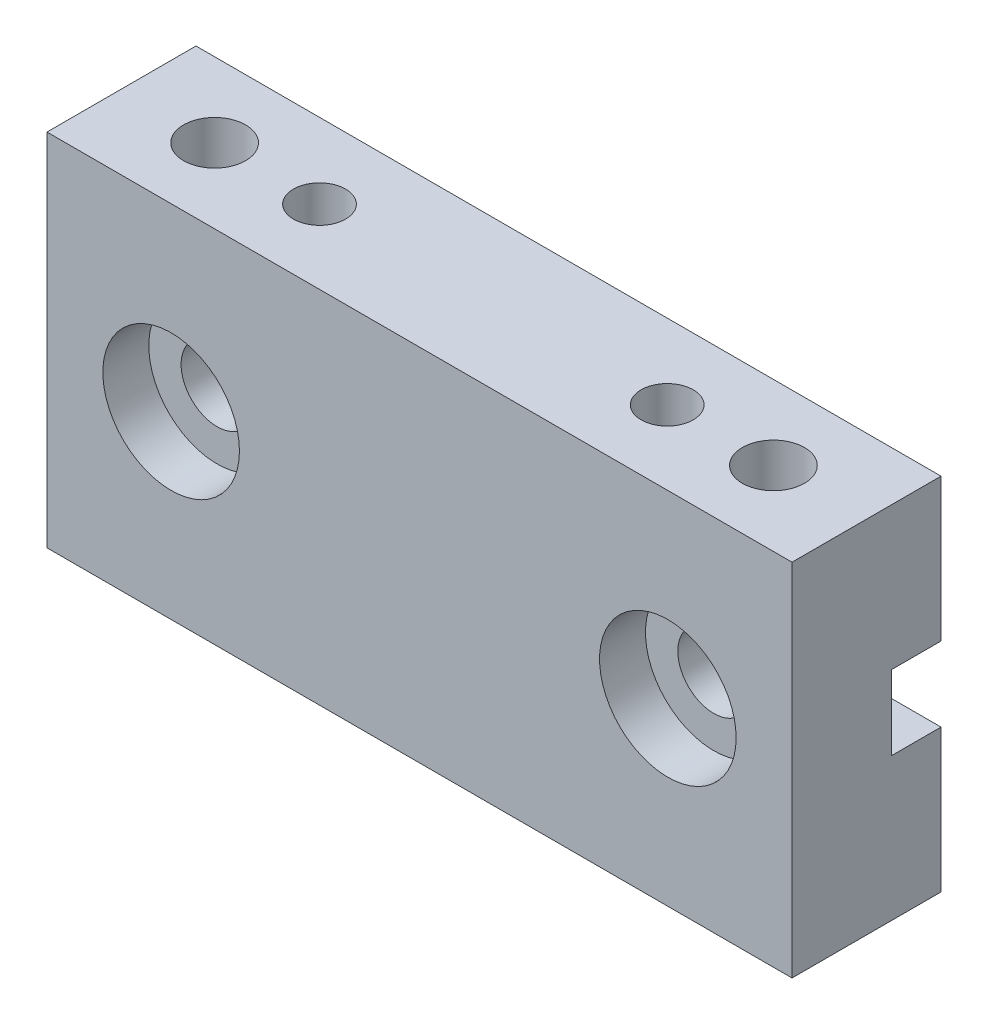
SolidWorks part; units mm, degrees
ref_plane "Front Plane" through (0, 0, 0) normal (0, 0, 1) x (1, 0, 0)
ref_plane "Top Plane" through (0, 0, 0) normal (0, 1, 0) x (1, 0, 0)
ref_plane "Right Plane" through (0, 0, 0) normal (1, 0, 0) x (0, 0, -1)
sketch "Sketch1" plane through (0, 0, 0) normal (0, 1, 0) x (1, 0, 0)
  line L1 (0, 0) -> (60, 0)
  line L2 (0, 0) -> (0, 12)
  line L3 (0, 12) -> (60, 12)
  line L4 (60, 0) -> (60, 12)
  dimension "D1" = 12
  dimension "D2" = 60
extrude "Boss-Extrude1" add sketch "Sketch1" along normal blind 11.5 contours L2 L3 L4 L1
sketch "Sketch4" plane through (0, 0, 0) normal (0, 1, 0) x (1, 0, 0)
  line L0 (60, 0) -> (60, 12) construction
  line L1 (0, 0) -> (60, 0)
  line L2 (0, 0) -> (0, 8)
  line L3 (0, 8) -> (60, 8)
  line L4 (60, 0) -> (60, 8)
  dimension "D1" = 8
extrude "Boss-Extrude2" add sketch "Sketch4" along normal blind 17.5 contours L3 L4 L1 L2
sketch "Sketch9" plane through (0, 0, 0) normal (1, 0, 0) x (0, 0, -1)
  line L1 (0, 17.5) -> (12, 17.5)
  line L2 (0, 17.5) -> (0, 29)
  line L3 (0, 29) -> (12, 29)
  line L4 (12, 17.5) -> (12, 29)
  dimension "D1" = 11.5
  dimension "D2" = 12
extrude "Boss-Extrude3" add sketch "Sketch9" along normal blind 60
sketch "Sketch10" plane through (0, 0, 0) normal (0, 0, 1) x (1, 0, 0)
  line L0 (60, 14.5) -> (0, 14.5) construction
  line L1 (60, 17.5) -> (60, 11.5) construction
  line L2 (0, 17.5) -> (0, 11.5) construction
  line L3 (50, 18.9581) -> (50, 10.0419) construction
  line L4 (10, 18.9581) -> (10, 10.0419) construction
  point P10 (-12.0778, 24.6861)
  point P11 (10, 14.5)
  point P12 (50, 14.5)
  dimension "D1" = 10
  dimension "D2" = 10
hole_wizard "CBORE for M5 Pan Head Screw2" positions "Sketch18" profile "Sketch17" counterbore size "M5" standard "DIN"
sketch "Sketch18" plane through (0, 0, 0) normal (0, 0, 1) x (1, 0, 0)
  line L0 (50, 18.9581) -> (50, 10.0419) construction
  line L1 (10, 18.9581) -> (10, 10.0419) construction
  point P0 (50, 14.5)
  point P4 (10, 14.5)
sketch "Sketch17" plane through (50, 14.5, 0) normal (1, 0, 0) x (0, -1, 0)
  line L0 (0, 0) -> (0, 9.9425)
  line L1 (0, 9.9425) -> (2.9, 8.2)
  line L2 (2.9, 8.2) -> (2.9, 3.7)
  line L3 (2.9, 3.7) -> (5.5, 3.7)
  line L4 (5.5, 3.7) -> (5.5, 0)
  line L5 (5.5, 0) -> (0, 0)
  line L10 (0, 9.9425) -> (-2.9, 8.2) construction
  line L11 (0, -6.35) -> (0, 107.95) construction
  dimension "Hole Dia." = 5.8
  dimension "Hole Depth" = 8.2
  dimension "C'Bore Dia." = 11
  dimension "C'Bore Depth" = 3.7
  dimension "Drill Angle" = 118
sketch "Sketch19" plane through (0, 0, 0) normal (0, 1, 0) x (1, 0, 0)
  line L0 (0, 6) -> (60, 6) construction
  line L1 (0, 12) -> (0, 0) construction
  line L2 (60, 12) -> (60, 0) construction
  line L3 (7.5, 9.0114) -> (7.5, 2.9886) construction
  line L4 (52.5, 9.0114) -> (52.5, 2.9886) construction
  point P10 (7.5, 6)
  point P12 (0, 0)
  point P13 (51.12, -50.8857)
  point P14 (63.1396, -47.6043)
  dimension "D1" = 45
  dimension "D2" = 7.5
hole_wizard "Ø5.0mm Dowel Hole7" positions "Sketch39" profile "Sketch40" hole size "Ø5.0" standard "ISO"
sketch "Sketch39" plane through (0, 29, 0) normal (0, 1, 0) x (1, 0, 0)
  line L0 (7.5, 9.0114) -> (7.5, 2.9886) construction
  point P0 (7.5, 6)
sketch "Sketch40" plane through (7.5, 29, -6) normal (1, 0, 0) x (0, 0, 1)
  line L0 (0, 0) -> (0, 10.5022)
  line L1 (0, 10.5022) -> (2.5, 9)
  line L2 (2.5, 9) -> (2.5, 0)
  line L5 (2.5, 0) -> (0, 0)
  line L10 (0, 10.5022) -> (-2.5, 9) construction
  line L11 (0, -6.35) -> (0, 107.95) construction
  dimension "Hole Dia." = 5
  dimension "Hole Depth" = 9
  dimension "Drill Angle" = 118
hole_wizard "Ø5.0mm Dowel Hole8" positions "Sketch41" profile "Sketch42" hole size "Ø5.0" standard "ISO"
sketch "Sketch41" plane through (0, 29, 0) normal (0, 1, 0) x (1, 0, 0)
  line L0 (52.5, 9.0114) -> (52.5, 2.9886) construction
  point P0 (52.5, 6)
sketch "Sketch42" plane through (52.5, 29, -6) normal (1, 0, 0) x (0, 0, 1)
  line L0 (0, 0) -> (0, 10.5022)
  line L1 (0, 10.5022) -> (2.5, 9)
  line L2 (2.5, 9) -> (2.5, 0)
  line L5 (2.5, 0) -> (0, 0)
  line L10 (0, 10.5022) -> (-2.5, 9) construction
  line L11 (0, -6.35) -> (0, 107.95) construction
  dimension "Hole Dia." = 5
  dimension "Hole Depth" = 9
  dimension "Drill Angle" = 118
sketch "Sketch43" plane through (0, 0, 0) normal (0, 1, 0) x (1, 0, 0)
  line L0 (16, 3.3768) -> (16, 8.5194) construction
  line L1 (44, 3.3768) -> (44, 8.5194) construction
  line L2 (0, 6) -> (60, 6) construction
  line L4 (60, 0) -> (60, 12) construction
  dimension "D1" = 28
  dimension "D2" = 16
hole_wizard "M5 Tapped Hole2" positions "Sketch49" profile "Sketch48" tap size "M5" standard "ISO"
sketch "Sketch49" plane through (0, 29, 0) normal (0, 1, 0) x (1, 0, 0)
  line L0 (16, 3.3768) -> (16, 8.5194) construction
  point P0 (16, 5.9481)
sketch "Sketch48" plane through (16, 29, -5.9481) normal (1, 0, 0) x (0, 0, 1)
  line L0 (0, 0) -> (0, 13.6618)
  line L1 (0, 13.6618) -> (2.1, 12.4)
  line L2 (2.1, 12.4) -> (2.1, 0)
  line L5 (2.1, 0) -> (0, 0)
  line L10 (0, 13.6618) -> (-2.1, 12.4) construction
  line L11 (0, -6.35) -> (0, 107.95) construction
  dimension "Tap Drill Dia." = 4.2
  dimension "Tap Drill Depth" = 12.4
  dimension "Drill Angle" = 118
cosmetic thread "Hole Thread2" parameters "D1"=10, "D2"=5
hole_wizard "M5 Tapped Hole3" positions "Sketch50" profile "Sketch51" tap size "M5" standard "ISO"
sketch "Sketch50" plane through (0, 29, 0) normal (0, 1, 0) x (1, 0, 0)
  line L0 (44, 3.3768) -> (44, 8.5194) construction
  point P0 (44, 5.9481)
sketch "Sketch51" plane through (44, 29, -5.9481) normal (1, 0, 0) x (0, 0, 1)
  line L0 (0, 0) -> (0, 13.6618)
  line L1 (0, 13.6618) -> (2.1, 12.4)
  line L2 (2.1, 12.4) -> (2.1, 0)
  line L5 (2.1, 0) -> (0, 0)
  line L10 (0, 13.6618) -> (-2.1, 12.4) construction
  line L11 (0, -6.35) -> (0, 107.95) construction
  dimension "Tap Drill Dia." = 4.2
  dimension "Tap Drill Depth" = 12.4
  dimension "Drill Angle" = 118
cosmetic thread "Hole Thread3" parameters "D1"=10, "D2"=5
